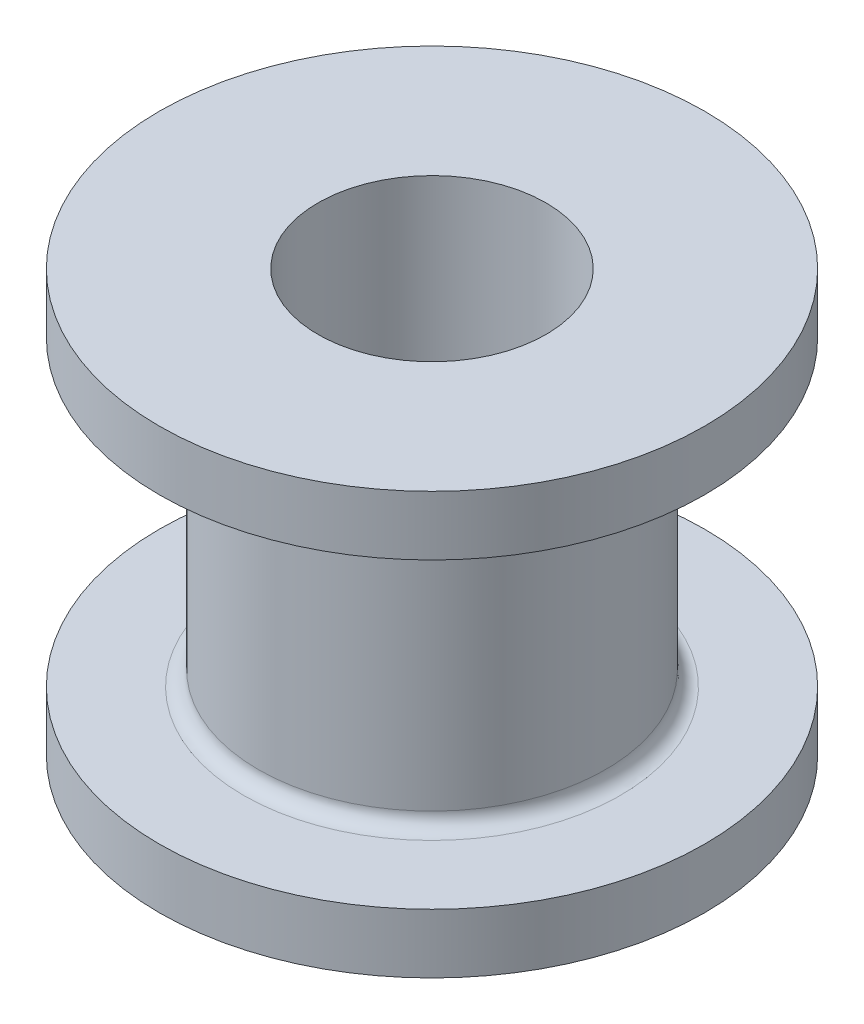
SolidWorks part; units mm, degrees
ref_plane "Front Plane" through (0, 0, 0) normal (0, 0, 1) x (1, 0, 0)
ref_plane "Top Plane" through (0, 0, 0) normal (0, 1, 0) x (1, 0, 0)
ref_plane "Right Plane" through (0, 0, 0) normal (1, 0, 0) x (0, 0, -1)
sketch "Sketch1" plane through (0, 0, 0) normal (0, 0, 1) x (1, 0, 0)
  line L0 (0, 0) -> (0, 85) construction
  line L1 (23, 85) -> (55, 85)
  line L2 (55, 85) -> (55, 73)
  line L3 (55, 73) -> (35, 73)
  line L4 (35, 73) -> (35, 12)
  line L5 (35, 12) -> (55, 12)
  line L6 (55, 12) -> (55, 0)
  line L7 (55, 0) -> (23, 0)
  line L8 (23, 85) -> (23, 0)
  dimension "D1" = 85
  dimension "D2" = 110
  dimension "D3" = 12
  dimension "D4" = 12
  dimension "D5" = 46
  dimension "D6" = 12
revolve "Revolve1" add sketch "Sketch1" angle 360 about L0
fillet "Fillet1" radius 3 2 edges at (0, 73, -35) (0, 12, -35)
